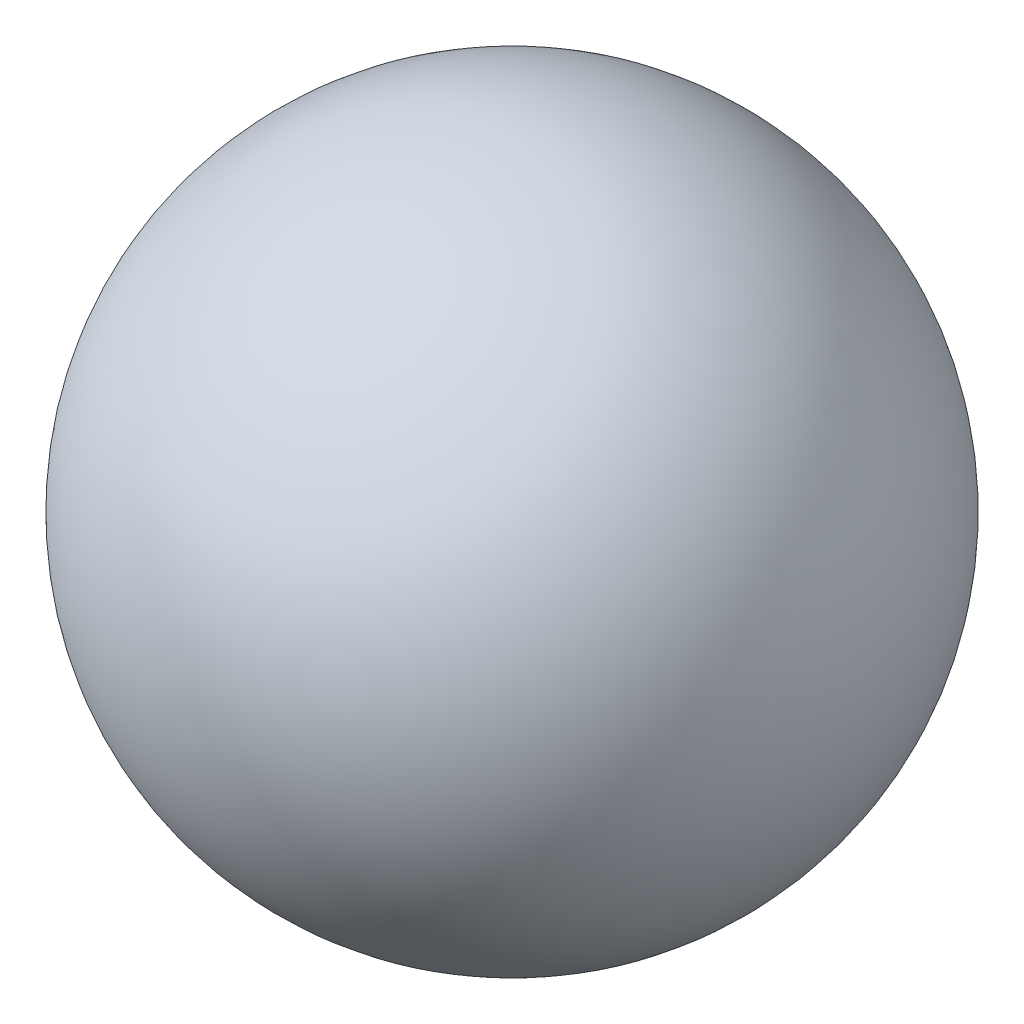
SolidWorks part; units mm, degrees
ref_plane "Front" through (0, 0, 0) normal (0, 0, 1) x (1, 0, 0)
ref_plane "Top" through (0, 0, 0) normal (0, 1, 0) x (1, 0, 0)
ref_plane "Right" through (0, 0, 0) normal (1, 0, 0) x (0, 0, -1)
sketch "Sketch1" plane through (0, 0, 0) normal (0, 0, 1) x (1, 0, 0)
  line L0 (0, 30.1625) -> (0, -30.1625) construction
  line L1 (0, 30.1625) -> (0, -30.1625)
  arc A0 (0, 30.1625) -> (0, -30.1625) centre (0, 0) ccw
  dimension "D1" = 60.325
revolve "Revolve1" add sketch "Sketch1" angle 360 about L0
